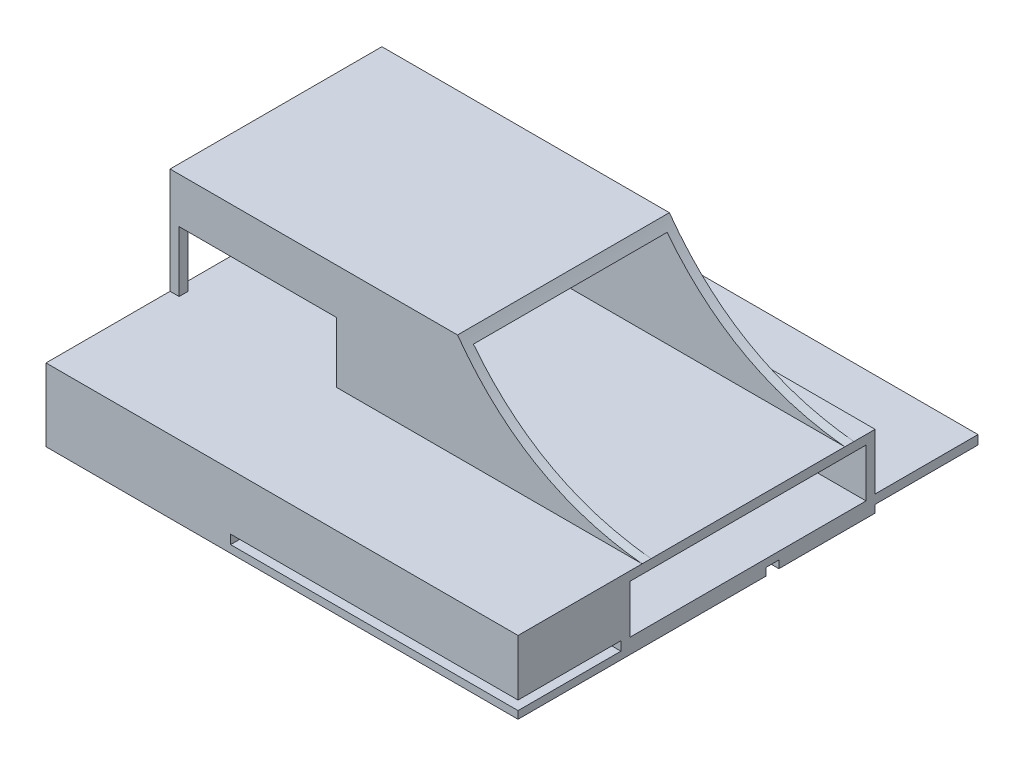
SolidWorks part; units mm, degrees
ref_plane "Plan de face" through (0, 0, 0) normal (0, 0, 1) x (1, 0, 0)
ref_plane "Plan de dessus" through (0, 0, 0) normal (0, 1, 0) x (1, 0, 0)
ref_plane "Plan de droite" through (0, 0, 0) normal (1, 0, 0) x (0, 0, -1)
sketch "Esquisse1" plane through (0, 0, 0) normal (0, 1, 0) x (1, 0, 0)
  line L0 (-54.2982, 57.973) -> (101.7018, 57.973)
  line L1 (-54.2982, 57.973) -> (-54.2982, -26.027)
  line L2 (101.7018, 57.973) -> (101.7018, -26.027)
  line L3 (-54.2982, -26.027) -> (101.7018, -26.027)
  dimension "D1" = 156
  dimension "D2" = 84
extrude "Boss.-Extru.1" add sketch "Esquisse1" along normal blind 59
sketch "Esquisse2" plane through (101.7018, 0, 0) normal (1, 0, 0) x (0, 0, -1)
  line L0 (57.973, 0) -> (57.973, 5)
  line L1 (57.973, 59) -> (57.973, 0) construction
  line L2 (57.973, 5) -> (-26.027, 5)
  line L3 (-26.027, 59) -> (-26.027, 0) construction
  line L4 (-26.027, 5) -> (-26.027, 0)
  line L6 (15.973, 0) -> (21.973, 0)
  line L7 (21.973, 0) -> (21.973, 2.5)
  line L8 (21.973, 2.5) -> (26.173, 2.5)
  line L9 (26.173, 2.5) -> (26.173, 0)
  line L11 (-26.027, 5) -> (-23.027, 5)
  line L12 (-23.027, 5) -> (-23.027, 21)
  line L13 (-23.027, 21) -> (54.973, 21)
  line L14 (54.973, 21) -> (54.973, 5)
  line L15 (54.973, 21) -> (54.973, 24)
  line L16 (54.973, 24) -> (-26.027, 24)
  line L17 (-26.027, 24) -> (57.973, 24)
  line L18 (15.973, 24) -> (47.973, 24)
  line L19 (47.973, 24) -> (47.973, 56)
  line L20 (47.973, 56) -> (-16.027, 56)
  line L21 (-16.027, 56) -> (-16.027, 24)
  line L22 (-16.027, 24) -> (47.973, 24)
  line L23 (47.973, 24) -> (50.973, 24)
  line L24 (50.973, 24) -> (50.973, 59)
  line L25 (-26.027, 59) -> (57.973, 59) construction
  line L26 (-16.027, 24) -> (-19.027, 24)
  line L27 (-19.027, 24) -> (-19.027, 59)
  line L28 (-19.027, 59) -> (50.973, 59)
  line L29 (57.973, 59) -> (57.973, 24)
  line L30 (50.973, 59) -> (57.973, 59)
  line L31 (-19.027, 59) -> (-26.027, 59)
  line L32 (-26.027, 59) -> (-26.027, 24)
  line L33 (21.973, 0) -> (26.173, 0)
  line M8 (-26.027, 0) -> (57.973, 0)
  line M9 (57.973, 0) -> (57.973, 59)
  line M10 (57.973, 59) -> (-26.027, 59)
  line M11 (-26.027, 59) -> (-26.027, 0)
  dimension "D1" = 84
extrude "Enlèv. mat.-Extru.1" cut sketch "Esquisse2" against normal through all contours L20 L21 L16 L17 L19 | L14 L13 L12 L2 | L16 L27 M10 M11 | L24 L16 L17 M9 M10 | L9 L8 L7 M8
sketch "Esquisse3" plane through (0, 0, 19.027) normal (0, 0, 1) x (1, 0, 0)
  line L0 (-54.2982, 59) -> (40.7018, 59)
  line L1 (-54.2982, 59) -> (101.7018, 59) construction
  line L2 (40.7018, 59) -> (40.7018, 24)
  line L3 (-54.2982, 24) -> (101.7018, 24) construction
  line L4 (40.7018, 24) -> (-54.2982, 24)
  line L5 (-54.2982, 24) -> (-54.2982, 59) construction
  line L6 (-54.2982, 24) -> (-54.2982, 59)
  line L7 (40.7018, 59) -> (101.7018, 59)
  line L8 (101.7018, 59) -> (101.7018, 24)
  line L9 (101.7018, 24) -> (40.7018, 24)
  spline S0 degree 2 poles (40.7018, 59) (63.2327, 27.7967) (101.7018, 24) knots 0 0 0 1 1 1
  line M1 (101.7018, 24) -> (101.7018, 59)
  line M2 (101.7018, 59) -> (-54.2982, 59)
extrude "Enlèv. mat.-Extru.3" cut sketch "Esquisse3" against normal through all contours S0 M2 M1
sketch "Esquisse4" plane through (0, 0, 19.027) normal (0, 0, 1) x (1, 0, 0)
  line L0 (-54.2982, 24) -> (-51.2982, 24)
  line L1 (-54.2982, 24) -> (101.7018, 24) construction
  line L2 (-51.2982, 24) -> (-51.2982, 44)
  line L3 (-51.2982, 44) -> (0.7018, 44)
  line L4 (0.7018, 44) -> (0.7018, 24)
  line L5 (0.7018, 24) -> (-51.2982, 24)
  line M1 (-54.2982, 24) -> (101.7018, 24)
extrude "Enlèv. mat.-Extru.4" cut sketch "Esquisse4" against normal blind 59 contours L4 L3 L2 M1
sketch "Esquisse5" plane through (0, 0, -57.973) normal (0, 0, -1) x (-1, 0, 0)
  line L0 (54.2982, 0) -> (54.2982, 2.5)
  line L1 (54.2982, 24) -> (54.2982, 0) construction
  line L2 (54.2982, 2.5) -> (54.2982, 5.5)
  line L3 (54.2982, 0) -> (-40.7018, 0)
  line L4 (-101.7018, 0) -> (54.2982, 0) construction
  line L5 (-40.7018, 0) -> (-40.7018, 5.5)
  line L7 (54.2982, 2.5) -> (-40.7018, 2.75)
  line L9 (-101.7018, 24) -> (-101.7018, 0) construction
  line L10 (-101.7018, 5.5) -> (-101.7018, 2.5)
  line L11 (-101.7018, 2.5) -> (-40.7018, 2.75)
  line L12 (-101.7018, 5.5) -> (-6.7018, 5.5)
  line L13 (-6.7018, 5.5) -> (-6.7018, 2.6605)
  line M7 (-101.7018, 24) -> (-101.7018, 0)
extrude "Boss.-Extru.2" add sketch "Esquisse5" along normal blind 34 contours L12 L11 L5 M7 | L13 L12 L5 L7
sketch "Esquisse6" plane through (0, 0, 26.027) normal (0, 0, 1) x (1, 0, 0)
  line L0 (-54.2982, 0) -> (-54.2982, 2.5)
  line L1 (-54.2982, 24) -> (-54.2982, 0) construction
  line L2 (-54.2982, 2.5) -> (-54.2982, 5.5)
  line L6 (101.7018, 0) -> (101.7018, 2.5)
  line L7 (101.7018, 24) -> (101.7018, 0) construction
  line L8 (101.7018, 2.5) -> (101.7018, 5.5)
  line L9 (101.7018, 5.5) -> (6.7018, 5.5)
  line L10 (6.7018, 5.5) -> (6.7018, 2.5)
  line L11 (6.7018, 2.5) -> (101.7018, 2.5)
extrude "Boss.-Extru.3" add sketch "Esquisse6" along normal blind 34
